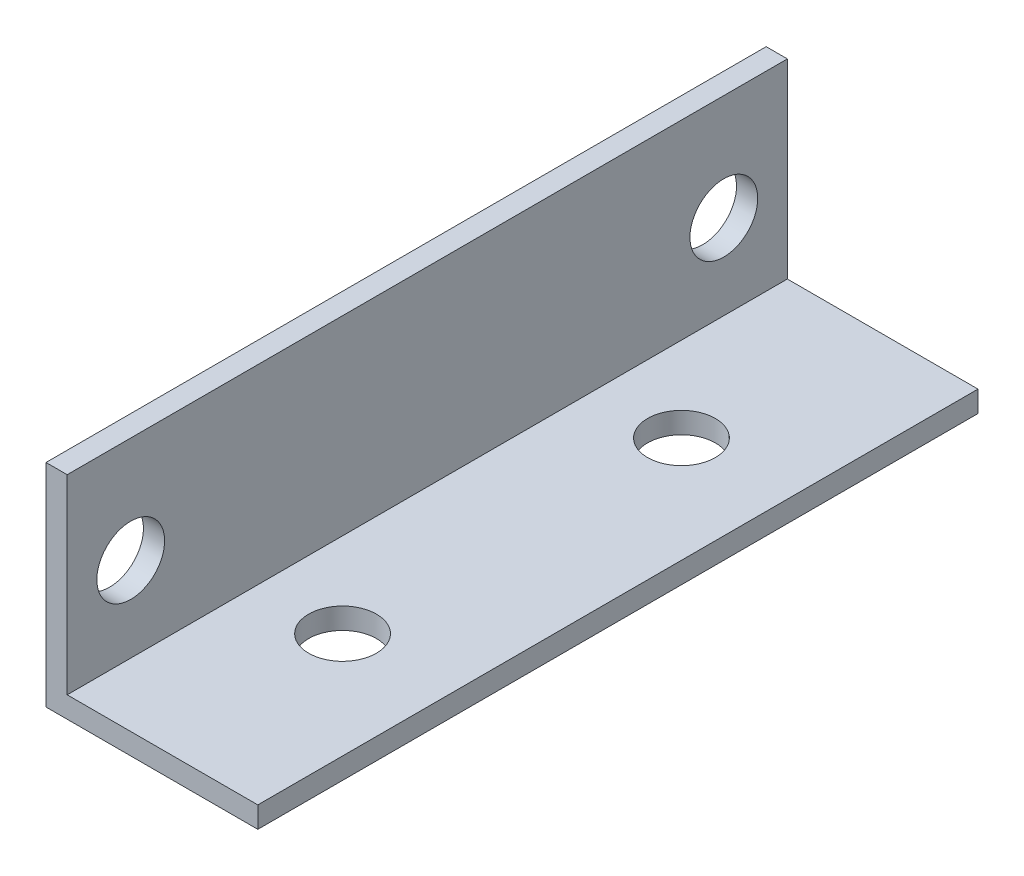
SolidWorks part; units mm, degrees
material "6063-T5"
ref_plane "正面" through (0, 0, 0) normal (0, 0, 1) x (1, 0, 0)
ref_plane "平面" through (0, 0, 0) normal (0, 1, 0) x (1, 0, 0)
ref_plane "右側面" through (0, 0, 0) normal (1, 0, 0) x (0, 0, -1)
sketch "ｽｹｯﾁ1" plane through (0, 0, 0) normal (0, 0, 1) x (1, 0, 0)
  line L0 (-5, 5) -> (5, -5) construction
  line L1 (5, -5) -> (-5, -5)
  line L2 (-5, -5) -> (-5, 5)
  dimension "D1" = 10
extrude "押し出し-薄板1" add sketch "ｽｹｯﾁ1" along normal mid plane 34 thin
sketch "ｽｹｯﾁ2" plane through (-5, 0, 0) normal (-1, 0, 0) x (0, 0, 1)
  line L0 (-17, 0) -> (17, 0) construction
  line L1 (-17, -5) -> (-17, 5) construction
  line L2 (17, -5) -> (17, 5) construction
  line L4 (17, 5) -> (-17, 5) construction
  line L5 (0, 5) -> (0, -5) construction
  line L6 (17, -5) -> (-17, -5) construction
  circle A0 centre (-14, 0) radius 1.6
  circle A1 centre (14, 0) radius 1.6
  dimension "D1" = 3.2
  dimension "D2" = 3
extrude "ｶｯﾄ - 押し出し1" cut sketch "ｽｹｯﾁ2" against normal through all
sketch "ｽｹｯﾁ3" plane through (0, -5, 0) normal (0, -1, 0) x (1, 0, 0)
  line L0 (0, -17) -> (0, 17) construction
  line L1 (5, -17) -> (-5, -17) construction
  line L2 (5, 17) -> (-5, 17) construction
  line L4 (5, 17) -> (5, -17) construction
  line L5 (5, 0) -> (-5, 0) construction
  line L6 (-5, 17) -> (-5, -17) construction
  circle A0 centre (0, -8) radius 1.6
  circle A1 centre (0, 8) radius 1.6
  dimension "D1" = 3.2
  dimension "D2" = 9
extrude "ｶｯﾄ - 押し出し2" cut sketch "ｽｹｯﾁ3" against normal through all
